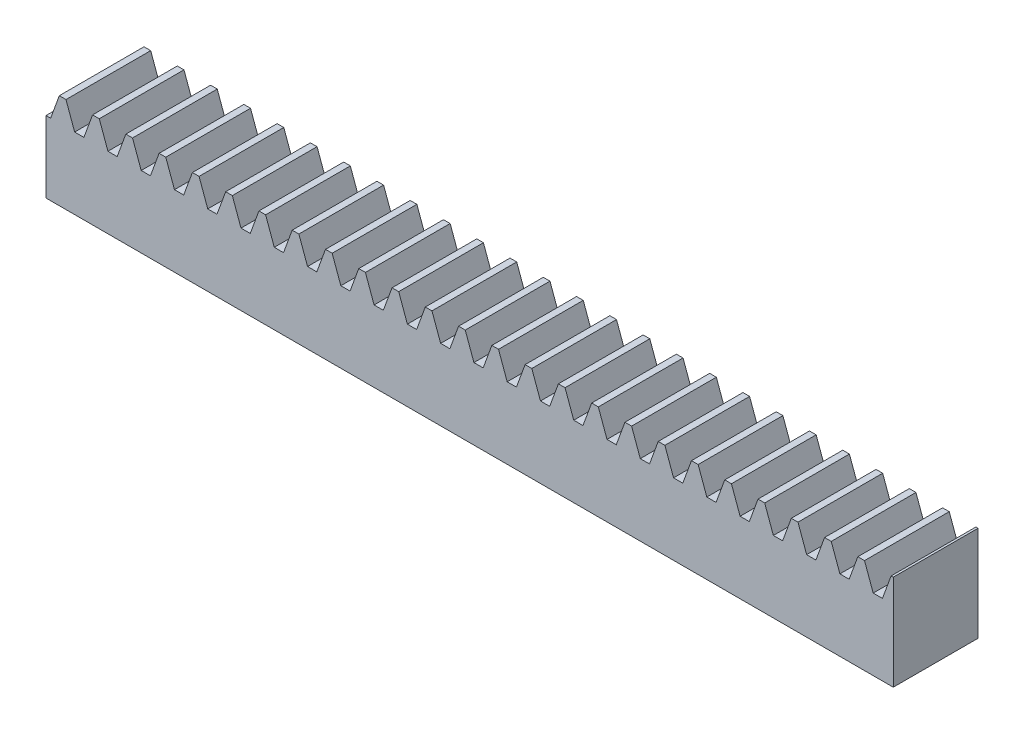
SolidWorks part; units mm, degrees
extrude "Blank" add sketch "BlankSke" against normal blind 12
sketch "BlankSke" plane through (0, 0, 0) normal (0, 0, 1) x (1, 0, 0)
  line L1 (0, 0) -> (120, 0)
  line L2 (0, 0) -> (0, 13.5)
  line L3 (0, 13.5) -> (120, 13.5)
  line L4 (120, 0) -> (120, 13.5)
  dimension "Length" = 120
  dimension "Blank_height" = 13.5
ref_plane "Plane1" through (0, 0, 0) normal (0, 0, 1) x (1, 0, 0)
ref_plane "Plane2" through (0, 0, 0) normal (0, 1, 0) x (1, 0, 0)
ref_plane "Plane3" through (0, 0, 0) normal (1, 0, 0) x (0, 0, -1)
other "Configuration Table"
sketch "HoldingSke" plane through (0, 0, 0) normal (0, 1, 0) x (1, 0, 0)
  line L0 (0, 0) -> (0.0928, 0.6602)
  line L1 (-15, 0) -> (100, 0) construction
  line L2 (0, 0) -> (-2.1039, 2.3779)
  line L3 (0, 0) -> (-11.863, 4.5341)
  line L4 (0, 0) -> (7.6947, 3.9206)
  line L5 (0, 0) -> (-23.7986, -8.8762)
  line L6 (0, 0) -> (-10.5278, -7.1032)
  line L9 (-71.009, 38.7566) -> (41.7541, 79.799)
  line L10 (-76.2, 3.8779) -> (-64.2, 3.8779)
  line L11 (0, 0) -> (-12, 0)
  line L12 (-76.2, 101.6) -> (-76.147, 101.6)
  line L13 (24.9733, 27.94) -> (52.9518, 28.4284)
  line L14 (24.9733, 27.94) -> (24.9743, 27.94)
  line L15 (24.9733, 27.94) -> (100.4006, 29.5858)
  circle A0 centre (0, 0) radius 19.05
  circle A1 centre (0, 0) radius 6
  circle A2 centre (0, 0) radius 12.7
  dimension "MPH" = 12
  dimension "Diameter" = 38.1
  dimension "Num_teeth" = 27
  dimension "Pitch" = 0.6667
  dimension "Show_teeth" = 998
  dimension "Thickness" = 12.7
  dimension "Ap" = 20
  dimension "Pitch_height" = 12
  dimension "Width" = 12
  dimension "Backlash" = 0.053
  dimension "Addendum_fac" = 1
  dimension "Dedendum_fac" = 1.25
  dimension "Clearance_fac" = 0.25
  dimension "Dedendum_add" = 0.001
  dimension "Length" = 120
  dimension "Module" = 1.5
sketch "TooCutSkeIll" plane through (0, 0, 0) normal (0, 0, 1) x (1, 0, 0)
  line L0 (-1.8687, 13.4605) -> (-0.7447, 10.3724)
  line L1 (-0.3914, 10.125) -> (0.3914, 10.125)
  line L2 (0.7447, 10.3724) -> (1.8687, 13.4605)
  line L3 (120, 13.5) -> (0, 13.5) construction
  line L4 (0, 0) -> (0, 64.897) construction
  line L5 (-13.208, 12) -> (12.954, 12) construction
  line L6 (0, 0) -> (120, 0) construction
  line L7 (1.3371, 12) -> (1.3371, 48.7463) construction
  line L8 (-1.3371, 12) -> (-1.3371, 48.7463) construction
  line L9 (1.9251, 13.5) -> (1.9251, 13.5254)
  line L10 (-1.9251, 13.5) -> (-1.9251, 13.5254)
  line L11 (-1.9251, 13.5254) -> (1.9251, 13.5254)
  arc A0 (0.3914, 10.125) -> (0.7447, 10.3724) centre (0.3914, 10.501) ccw
  arc A1 (-0.7447, 10.3724) -> (-0.3914, 10.125) centre (-0.3914, 10.501) ccw
  arc A2 (1.9251, 13.5) -> (1.8687, 13.4605) centre (1.9251, 13.44) ccw
  arc A3 (-1.8687, 13.4605) -> (-1.9251, 13.5) centre (-1.9251, 13.44) ccw
  dimension "Pitch_height" = 12
  dimension "Addendum_plus" = 1.5254
  dimension "Pressure_angle" = 20
  dimension "Gap_width" = 2.6742
  dimension "Dedendum" = 1.875
extrude "ToothCutIll" [suppressed] cut sketch "TooCutSkeIll" against normal through all
sketch "TooCutSkeSim" plane through (0, 0, 0) normal (0, 0, 1) x (1, 0, 0)
  line L0 (0.6547, 10.125) -> (-0.6547, 10.125)
  line L1 (1.8923, 13.5254) -> (0.6547, 10.125)
  line L2 (0, 17.4625) -> (0, 53.467) construction
  line L3 (1.8923, 13.5254) -> (-1.8923, 13.5254)
  line L6 (-1.8923, 13.5254) -> (-0.6547, 10.125)
  line L9 (-1.3371, 12) -> (1.3371, 12) construction
  line L10 (0, 0) -> (120, 0) construction
  line L11 (1.3371, 12) -> (1.3371, 53.467) construction
  line L12 (-1.3371, 12) -> (-1.3371, 53.467) construction
  dimension "Pitch_height" = 12
  dimension "Addendum_plus" = 1.5254
  dimension "Pressure_angle" = 20
  dimension "Gap_width" = 2.6742
  dimension "Dedendum" = 1.875
extrude "ToothCutSim" cut sketch "TooCutSkeSim" against normal through all
pattern_linear "TeethCuts" count 26 spacing 4.7124 along (1, 0, 0) of "ToothCutIll", "ToothCutSim"
equation "' \"Module@HoldingSke\" = 6.35"
equation "' \"Num_teeth@HoldingSke\" = 12"
equation "' \"Ap@HoldingSke\" =  20"
equation "' \"Ap@HoldingSke\" = 20"
equation "' \"Width@HoldingSke\" = 0.25 * 25.4"
equation "' \"Show_teeth@HoldingSke\" = 500"
equation "' \"Backlash@HoldingSke\" = 0.009 * 25.4"
equation "' \"Addendum_fac@HoldingSke\" = 1.0"
equation "' \"Dedendum_fac@HoldingSke\" = 1.25"
equation "' \"Dedendum_add@HoldingSke\" = 0.00005 * 25.4"
equation "' \"Clearance_fac@HoldingSke\" = 0.25"
equation "' \"Pitch_height@HoldingSke\" = 1 * 25.4"
equation "' \"Length@HoldingSke\" = 4.71 * 25.4"
equation "\"Pitch@HoldingSke\" = 1 / \"Module@HoldingSke\""
equation "\"MPH@HoldingSke\" = \"Dedendum_fac@HoldingSke\" / \"Pitch@HoldingSke\" + 2 * \"Dedendum_add@HoldingSke\" + 0.002 * 25.4"
equation "\"MPH@HoldingSke\" = ((sgn( \"MPH@HoldingSke\" - \"Pitch_height@HoldingSke\")+1)*( \"MPH@HoldingSke\" - \"Pitch_height@HoldingSke\"))/2 + \"Pitch_height@HoldingSke\""
equation "\"Blank_height@BlankSke\" = \"Pitch_height@HoldingSke\" + \"Addendum_fac@HoldingSke\"  / \"Pitch@HoldingSke\" "
equation "\"Length@BlankSke\" =  \"Length@HoldingSke\""
equation "\"Face_width@Blank\" = \"Width@HoldingSke\""
equation "\"Pressure_angle@TooCutSkeIll\" = \"Ap@HoldingSke\""
equation "\"Addendum_plus@TooCutSkeIll\" =  \"Addendum_fac@HoldingSke\"  / \"Pitch@HoldingSke\" + 0.001 *25.4"
equation "\"Dedendum@TooCutSkeIll\" = \"Dedendum_fac@HoldingSke\"  / \"Pitch@HoldingSke\""
equation "\"Pitch_height@TooCutSkeIll\" =  \"MPH@HoldingSke\""
equation "\"Gap_width@TooCutSkeIll\" = 3.14159265 / 2 / \"Pitch@HoldingSke\" + 6 * \"Backlash@HoldingSke\""
equation "\"Pressure_angle@TooCutSkeSim\" = \"Ap@HoldingSke\""
equation "\"Addendum_plus@TooCutSkeSim\" =  \"Addendum_fac@HoldingSke\"  / \"Pitch@HoldingSke\" + 0.001 * 25.4"
equation "\"Dedendum@TooCutSkeSim\" = \"Dedendum_fac@HoldingSke\"  / \"Pitch@HoldingSke\""
equation "\"Pitch_height@TooCutSkeSim\" =  \"MPH@HoldingSke\""
equation "\"Gap_width@TooCutSkeSim\" = 3.14159265 / 2 / \"Pitch@HoldingSke\" + 6 * \"Backlash@HoldingSke\""
equation "\"Root_fillet@TooCutSkeIll\" = \"Clearance_fac@HoldingSke\" / \"Pitch@HoldingSke\" + \"Dedendum_add@HoldingSke\""
equation "\"Break_rad@TooCutSkeIll\" = 0.02 / \"Pitch@HoldingSke\" * 2"
equation "\"Linear_pitch@TeethCuts\" = 3.14159265 / \"Pitch@HoldingSke\""
equation "\"Num_teeth@HoldingSke\" = int( ( \"Length@HoldingSke\" + 0 ) / (3.14159265 / \"Pitch@HoldingSke\")) + 0.9999  + 1"
equation " \"Num_teeth@TeethCuts\" = int( \"Show_teeth@HoldingSke\" ) + 1"
equation " \"Num_teeth@TeethCuts\" = ((sgn( \"Num_teeth@TeethCuts\" - \"Num_teeth@HoldingSke\" )-1)*( \"Num_teeth@TeethCuts\" - \"Num_teeth@HoldingSke\" ))/-2+ \"Num_teeth@HoldingSke\""
equation " \"Num_teeth@TeethCuts\" = ((sgn( \"Num_teeth@TeethCuts\" - 2.0)+1)*( \"Num_teeth@TeethCuts\" - 2.0))/2 +2.0"
